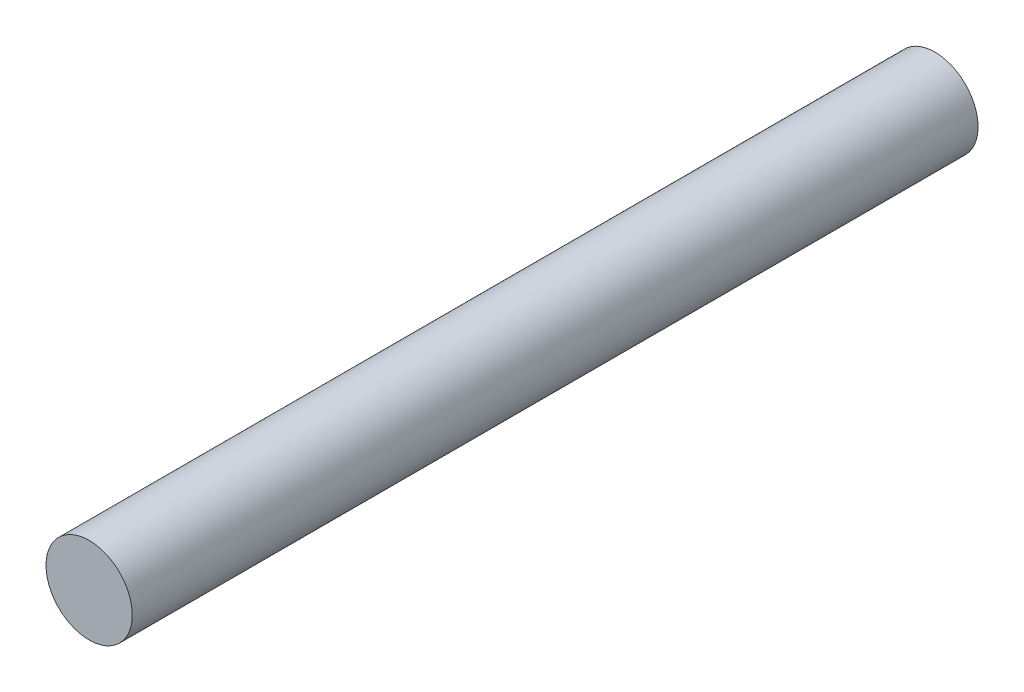
SolidWorks part; units mm, degrees
ref_plane "Front" through (0, 0, 0) normal (0, 0, 1) x (1, 0, 0)
ref_plane "Top" through (0, 0, 0) normal (0, 1, 0) x (1, 0, 0)
ref_plane "Right" through (0, 0, 0) normal (1, 0, 0) x (0, 0, -1)
sketch "Croquis1" plane through (0, 0, 0) normal (0, 1, 0) x (1, 0, 0)
  line L0 (0, 0) -> (0, 49)
  dimension "D1" = 49
other "7.10 sae 1010 barra redonda trefilado 5 MM(1)"
ref_plane "Plano1" through (0, 0, 0) normal (0, 0, -1) x (-1, 0, 0)
sketch "Sketch1" plane through (0, 0, 0) normal (0, 0, -1) x (-1, 0, 0)
  circle A1 centre (0, 0) radius 2.5
  point P1 (0, 2.5)
  point P3 (-2.5, 0)
  point P5 (0, -2.5)
  point P6 (2.5, 0)
  point P7 (0, 0)
  point P8 (0, 0)
  dimension "Out_dia" = 5
